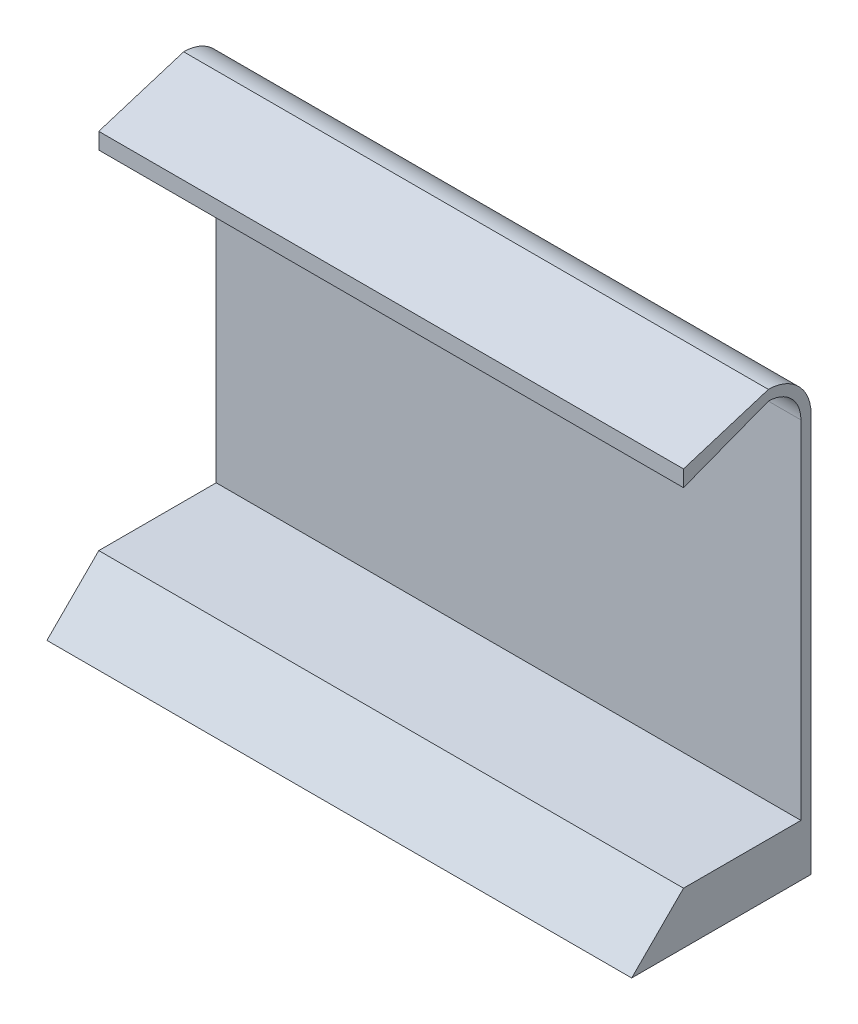
SolidWorks part; units mm, degrees
ref_plane "Front Plane" through (0, 0, 0) normal (0, 0, 1) x (1, 0, 0)
ref_plane "Top Plane" through (0, 0, 0) normal (0, 1, 0) x (1, 0, 0)
ref_plane "Right Plane" through (0, 0, 0) normal (1, 0, 0) x (0, 0, -1)
sketch "Sketch1" plane through (0, 0, 0) normal (1, 0, 0) x (0, 0, -1)
  line L0 (0, 16.231) -> (0, -315.2181)
  line L1 (0, -315.2181) -> (-112.1881, -315.2181)
  line L2 (0, -364.769) -> (9.7109, -364.769)
  line L3 (9.7109, -364.769) -> (9.7109, 16.231)
  line L5 (-112.1881, -315.2181) -> (-161.739, -364.769)
  line L6 (-161.739, -364.769) -> (0, -364.769)
  line L7 (-31.0748, 47.3058) -> (-112.1881, 16.231)
  line L8 (-112.1881, 16.231) -> (-112.1881, 31.7684)
  line L9 (-112.1881, 31.7684) -> (-31.0748, 57.0166)
  arc A0 (9.7109, 16.231) -> (-31.0748, 57.0166) centre (-31.0748, 16.231) ccw
  arc A1 (0, 16.231) -> (-31.0748, 47.3058) centre (-31.0748, 16.231) ccw
extrude "Boss-Extrude1" add sketch "Sketch1" along normal blind 558.8
